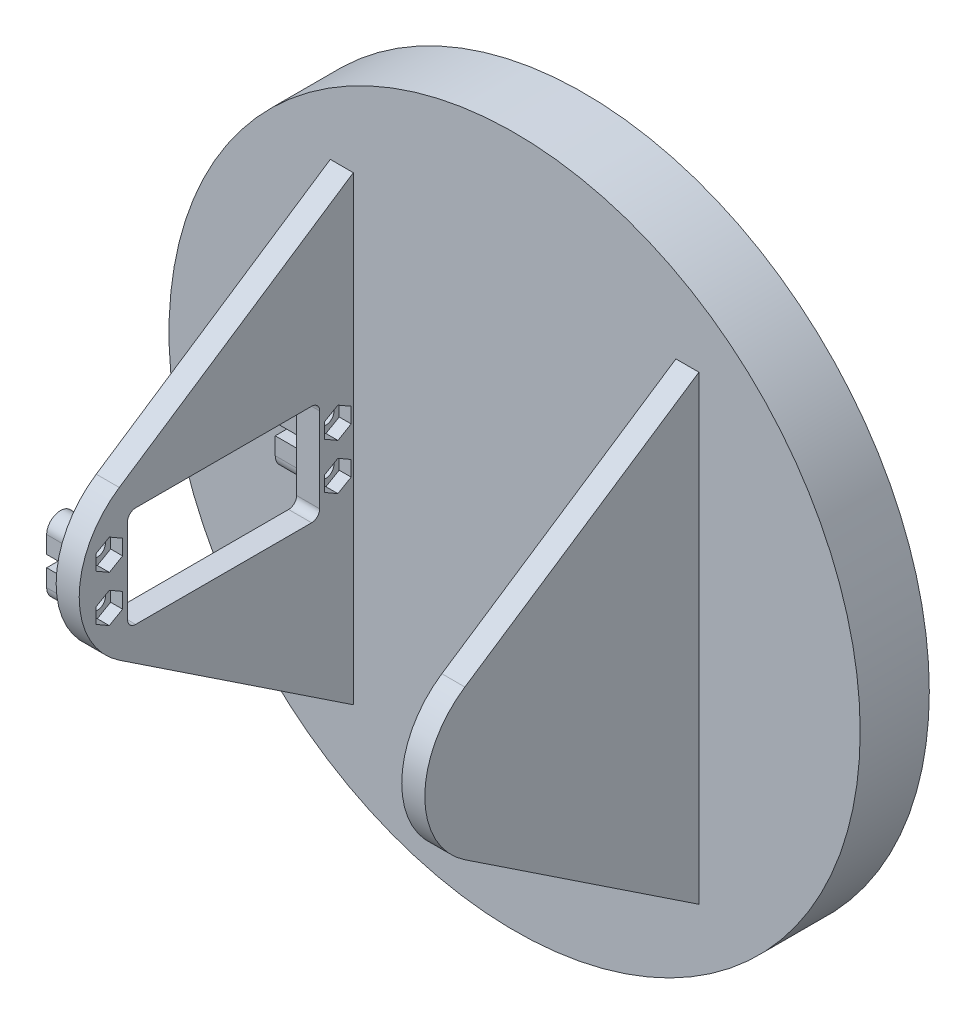
SolidWorks part; units mm, degrees
ref_plane "Front Plane" through (0, 0, 0) normal (0, 0, 1) x (1, 0, 0)
ref_plane "Top Plane" through (0, 0, 0) normal (0, 1, 0) x (1, 0, 0)
ref_plane "Right Plane" through (0, 0, 0) normal (1, 0, 0) x (0, 0, -1)
sketch "Sketch1" plane through (0, 0, 0) normal (0, 0, 1) x (1, 0, 0)
  circle A0 centre (0, 0) radius 75
  dimension "D1" = 150
extrude "Base Plate\\" add sketch "Sketch1" along normal blind 15
sketch "Sketch2" plane through (0, 0, 0) normal (0, 0, -1) x (-1, 0, 0)
  circle A0 centre (0, 0) radius 25 construction
  circle A1 centre (0, -25) radius 4.5
  circle A2 centre (-23.7764, -7.7254) radius 4.5
  circle A3 centre (-14.6946, 20.2254) radius 4.5
  circle A4 centre (14.6946, 20.2254) radius 4.5
  circle A5 centre (23.7764, -7.7254) radius 4.5
  point P16 (0, 0)
  dimension "D2" = 9
  dimension "D3" = 50
  dimension "D1" = 5
extrude "Drive Holes" cut sketch "Sketch2" against normal blind 10
chamfer "Chamfer1" distance 1 5 edges at (19.2764, -7.7254, 0) (10.1946, 20.2254, 0) (-19.1946, 20.2254, 0) (-28.2764, -7.7254, 0) (-4.5, -25, 0)
sketch "Sketch4" plane through (0, 0, 0) normal (1, 0, 0) x (0, 0, -1)
  line L0 (-15, 50) -> (-65.792, 16.2334)
  line L1 (-15, 75) -> (-15, -75) construction
  line L2 (-65.792, -16.2334) -> (-15, -50)
  line L3 (-15, -50) -> (-15, 50)
  arc A0 (-65.792, 16.2334) -> (-65.792, -16.2334) centre (-55, 0) ccw
  dimension "D1" = 100
  dimension "D2" = 40
extrude "Base Fin" add sketch "Sketch4" against normal blind 5 from offset 40
sketch "Sketch5" plane through (35, 0, 0) normal (-1, 0, 0) x (0, 0, 1)
  line L0 (15, 50) -> (15, -50)
  line L1 (15, -50) -> (65.792, -16.2334)
  line L2 (65.792, 16.2334) -> (15, 50)
  arc A0 (65.792, -16.2334) -> (65.792, 16.2334) centre (55, 0) ccw
extrude "Base Fin 2" add sketch "Sketch5" against normal blind 5 from offset 75
sketch "Sketch6" plane through (-40, 0, 0) normal (-1, 0, 0) x (0, 0, 1)
  line L0 (64, 8.8753) -> (64, -9.5247)
  line L1 (62.25, -11.2747) -> (24.05, -11.2747)
  line L2 (22.3, -9.5247) -> (22.3, 8.8753)
  line L3 (24.05, 10.6253) -> (62.25, 10.6253)
  arc A0 (64, -9.5247) -> (62.25, -11.2747) centre (62.25, -9.5247) cw
  arc A1 (24.05, -11.2747) -> (22.3, -9.5247) centre (24.05, -9.5247) cw
  arc A2 (22.3, 8.8753) -> (24.05, 10.6253) centre (24.05, 8.8753) cw
  arc A3 (62.25, 10.6253) -> (64, 8.8753) centre (62.25, 8.8753) cw
extrude "Cut-Extrude1" cut sketch "Sketch6" against normal up to next
sketch "Sketch7" plane through (-40, 0, 0) normal (-1, 0, 0) x (0, 0, 1)
  circle A0 centre (18.35, 4.6753) radius 1.75
  circle A1 centre (18.35, -5.3247) radius 1.75
  circle A2 centre (67.95, -5.3247) radius 1.75
  circle A3 centre (67.95, 4.6753) radius 1.75
  dimension "D1" = 3.5
extrude "Cut-Extrude2" cut sketch "Sketch7" against normal up to next
sketch "Sketch8" plane through (-40, 0, 0) normal (-1, 0, 0) x (0, 0, 1)
  line L0 (67.95, 4.6753) -> (67.95, -5.3247) construction
  line L1 (70.95, 4.6753) -> (70.95, -5.3247)
  line L2 (64.95, 4.6753) -> (64.95, -5.3247)
  line L3 (15, 7.6753) -> (15, 0)
  line L4 (15, -75) -> (15, 75) construction
  line L5 (15, 0) -> (15, -8.3247)
  line L6 (15, -8.3247) -> (18.35, -8.3247)
  line L7 (21.35, -5.3247) -> (21.35, 4.6753)
  line L8 (18.35, 7.6753) -> (15, 7.6753)
  arc A0 (70.95, 4.6753) -> (64.95, 4.6753) centre (67.95, 4.6753) ccw
  arc A1 (64.95, -5.3247) -> (70.95, -5.3247) centre (67.95, -5.3247) ccw
  arc A2 (18.35, -8.3247) -> (21.35, -5.3247) centre (18.35, -5.3247) ccw
  arc A3 (21.35, 4.6753) -> (18.35, 7.6753) centre (18.35, 4.6753) ccw
  circle A4 centre (18.35, 4.6753) radius 1.75 construction
  circle A5 centre (18.35, -5.3247) radius 1.75 construction
  point P4 (67.95, -0.3247)
  dimension "D1" = 3
  dimension "D2" = 3
extrude "Boss-Extrude1" add sketch "Sketch8" along normal up to surface (5.6 mm away)
sketch "Sketch9" plane through (-40, 0, 0) normal (1, 0, 0) x (0, 0, -1)
  circle A0 centre (-67.95, -5.3247) radius 1.75
  circle A1 centre (-67.95, 4.6753) radius 1.75
  circle A2 centre (-18.35, -5.3247) radius 1.75
  circle A3 centre (-18.35, 4.6753) radius 1.75
extrude "Cut-Extrude3" cut sketch "Sketch9" against normal up to surface (5.6 mm away) up to face at (-45.6, -0.3247, 18.4404)
sketch "Sketch10" plane through (-45.6, 0, 0) normal (-1, 0, 0) x (0, 0, 1)
  line L0 (21.35, 0.9253) -> (16.75, 0.9253)
  line L1 (21.35, 4.6753) -> (21.35, -5.3247) construction
  line L2 (16.75, 0.9253) -> (16.75, -1.5747)
  line L3 (16.75, -1.5747) -> (21.35, -1.5747)
  line L4 (23.05, 0.4253) -> (17.25, 0.4253) construction
  line L5 (17.25, -1.0747) -> (23.05, -1.0747) construction
  line L6 (17.25, 0.4253) -> (17.25, -1.0747) construction
  line L7 (21.35, 0.9253) -> (21.35, -1.5747)
  line L10 (64.95, -5.3247) -> (64.95, 4.6753) construction
  line L14 (64.95, -1.5747) -> (64.95, 0.9253)
  line L22 (64.95, 0.9253) -> (70.95, 0.9253)
  line L23 (70.95, 4.6753) -> (70.95, -5.3247) construction
  line L24 (70.95, 0.9253) -> (70.95, -1.5747)
  line L25 (70.95, -1.5747) -> (64.95, -1.5747)
  dimension "D1" = 0.5
  dimension "D2" = 0.5
  dimension "D3" = 0.5
extrude "Cut-Extrude4" cut sketch "Sketch10" against normal up to surface (5.6 mm away) up to face at (-40, -0.1948, 28.0928)
sketch "Sketch11" plane through (-35, 0, 0) normal (1, 0, 0) x (0, 0, -1)
  line L1 (-67.9442, -2.0049) -> (-70.8221, -3.6597)
  line L2 (-70.8221, -3.6597) -> (-70.8279, -6.9795)
  line L3 (-70.8279, -6.9795) -> (-67.9558, -8.6444)
  line L4 (-67.9558, -8.6444) -> (-65.0779, -6.9896)
  line L5 (-65.0779, -6.9896) -> (-65.0721, -3.6698)
  line L6 (-65.0721, -3.6698) -> (-67.9442, -2.0049)
  line L7 (-67.95, 7.9951) -> (-70.825, 6.3352)
  line L8 (-70.825, 6.3352) -> (-70.825, 3.0155)
  line L9 (-70.825, 3.0155) -> (-67.95, 1.3556)
  line L10 (-67.95, 1.3556) -> (-65.075, 3.0155)
  line L11 (-65.075, 3.0155) -> (-65.075, 6.3352)
  line L12 (-65.075, 6.3352) -> (-67.95, 7.9951)
  line L13 (-18.3535, -2.0049) -> (-21.2268, -3.6678)
  line L14 (-21.2268, -3.6678) -> (-21.2232, -6.9876)
  line L15 (-21.2232, -6.9876) -> (-18.3465, -8.6444)
  line L16 (-18.3465, -8.6444) -> (-15.4732, -6.9815)
  line L17 (-15.4732, -6.9815) -> (-15.4768, -3.6617)
  line L18 (-15.4768, -3.6617) -> (-18.3535, -2.0049)
  line L19 (-18.3554, 7.9951) -> (-21.2277, 6.3305)
  line L20 (-21.2277, 6.3305) -> (-21.2223, 3.0108)
  line L21 (-21.2223, 3.0108) -> (-18.3446, 1.3556)
  line L22 (-18.3446, 1.3556) -> (-15.4723, 3.0202)
  line L23 (-15.4723, 3.0202) -> (-15.4777, 6.3399)
  line L24 (-15.4777, 6.3399) -> (-18.3554, 7.9951)
  circle A0 centre (-67.95, -5.3247) radius 2.875 construction
  circle A1 centre (-67.95, 4.6753) radius 2.875 construction
  circle A2 centre (-18.35, -5.3247) radius 2.875 construction
  circle A3 centre (-18.35, 4.6753) radius 2.875 construction
  circle A4 centre (-18.35, 4.6753) radius 1.75 construction
  dimension "D1" = 5.75
extrude "Cut-Extrude5" cut sketch "Sketch11" against normal blind 2.6
